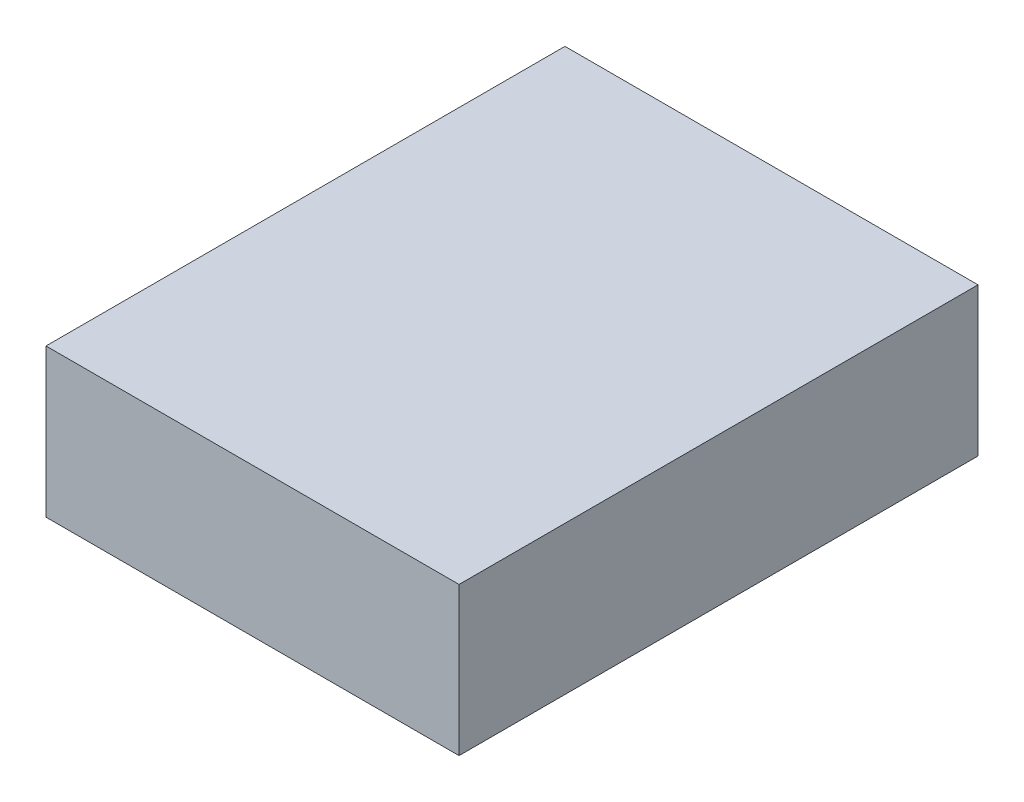
SolidWorks part; units mm, degrees
ref_plane "Front Plane" through (0, 0, 0) normal (0, 0, 1) x (1, 0, 0)
ref_plane "Top Plane" through (0, 0, 0) normal (0, 1, 0) x (1, 0, 0)
ref_plane "Right Plane" through (0, 0, 0) normal (1, 0, 0) x (0, 0, -1)
sketch "Sketch2" plane through (0, 0, 0) normal (0, 1, 0) x (1, 0, 0)
  line L1 (-79.657, 18.7515) -> (-40.657, 18.7515)
  line L2 (-79.657, 18.7515) -> (-79.657, -30.2485)
  line L3 (-79.657, -30.2485) -> (-40.657, -30.2485)
  line L4 (-40.657, 18.7515) -> (-40.657, -30.2485)
  dimension "D1" = 39
  dimension "D2" = 49
extrude "Boss-Extrude1" add sketch "Sketch2" along normal blind 14
